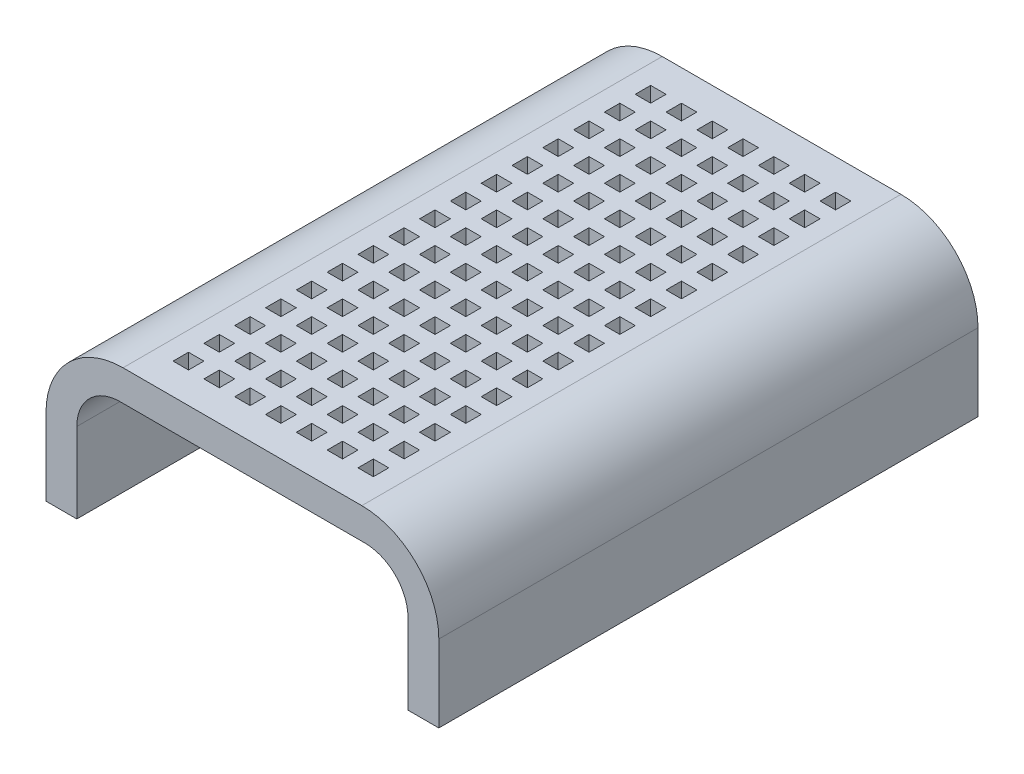
SolidWorks part; units mm, degrees
ref_plane "Plan de face" through (0, 0, 0) normal (0, 0, 1) x (1, 0, 0)
ref_plane "Plan de dessus" through (0, 0, 0) normal (0, 1, 0) x (1, 0, 0)
ref_plane "Plan de droite" through (0, 0, 0) normal (1, 0, 0) x (0, 0, -1)
sketch "Esquisse1" plane through (0, 0, 0) normal (0, 0, 1) x (1, 0, 0)
  line L0 (55, 0) -> (-55, 0) construction
  line L1 (-6.9124, 2) -> (8.5876, 2)
  line L2 (-11.9124, -3) -> (-11.9124, -8)
  line L3 (-11.9124, -8) -> (13.5876, -8)
  line L4 (13.5876, -3) -> (13.5876, -8)
  arc A0 (-6.9124, 2) -> (-11.9124, -3) centre (-6.9124, -3) ccw
  arc A1 (8.5876, 2) -> (13.5876, -3) centre (8.5876, -3) cw
  point P8 (13.5876, 2)
  point P19 (11.5876, 0)
  dimension "D3" = 5
  dimension "D4" = 5
  dimension "D1" = 25.5
  dimension "D2" = 10
extrude "Boss.-Extru.2" add sketch "Esquisse1" against normal blind 35 contours L2 A0 L1 A1 L4 L3
sketch "Esquisse2" plane through (0, 0, 0) normal (0, 0, 1) x (1, 0, 0)
  line L8 (-11.9124, -3) -> (-11.9124, -8) construction
  line L9 (-9.9124, -8) -> (11.5876, -8)
  line L10 (-9.9124, -8) -> (-9.9124, 0)
  line L11 (-9.9124, 0) -> (11.5876, 0)
  line L12 (11.5876, -8) -> (11.5876, 0)
  line L13 (-6.9124, 2) -> (8.5876, 2) construction
  line L14 (13.5876, -3) -> (13.5876, -8) construction
  line L15 (-11.9124, -8) -> (13.5876, -8) construction
  dimension "D1" = 2
  dimension "D2" = 2
  dimension "D3" = 2
extrude "Enlèv. mat.-Extru.1" cut sketch "Esquisse2" against normal up to surface (35 mm away) up to face at (0.8376, -2.6548, -35)
fillet "Congé1" radius 2.8 2 edges at (-9.9124, 0, -17.5) (11.5876, 0, -17.5)
sketch "Esquisse3" plane through (0, 2, 0) normal (0, 1, 0) x (1, 0, 0)
  line L0 (-6.9124, 35) -> (-6.9124, 0) construction
  line L1 (-5.6624, 33) -> (-4.6624, 33)
  line L2 (-5.6624, 33) -> (-5.6624, 32)
  line L3 (-5.6624, 32) -> (-4.6624, 32)
  line L4 (-4.6624, 33) -> (-4.6624, 32)
  line L6 (-3.6624, 33) -> (-3.6624, 32)
  line L7 (-6.9124, 35) -> (8.5876, 35) construction
  line L8 (-3.6624, 33) -> (-2.6624, 33)
  line L9 (-2.6624, 33) -> (-2.6624, 32)
  line L10 (-3.6624, 32) -> (-2.6624, 32)
  line L11 (-1.6624, 33) -> (-1.6624, 32)
  line L12 (-1.6624, 33) -> (-0.6624, 33)
  line L13 (-0.6624, 33) -> (-0.6624, 32)
  line L14 (-1.6624, 32) -> (-0.6624, 32)
  line L15 (0.3376, 33) -> (0.3376, 32)
  line L16 (0.3376, 33) -> (1.3376, 33)
  line L17 (1.3376, 33) -> (1.3376, 32)
  line L18 (0.3376, 32) -> (1.3376, 32)
  line L19 (2.3376, 33) -> (2.3376, 32)
  line L20 (2.3376, 33) -> (3.3376, 33)
  line L21 (3.3376, 33) -> (3.3376, 32)
  line L22 (2.3376, 32) -> (3.3376, 32)
  line L23 (4.3376, 33) -> (4.3376, 32)
  line L24 (4.3376, 33) -> (5.3376, 33)
  line L25 (5.3376, 33) -> (5.3376, 32)
  line L26 (4.3376, 32) -> (5.3376, 32)
  line L27 (6.3376, 33) -> (6.3376, 32)
  line L28 (6.3376, 33) -> (7.3376, 33)
  line L29 (7.3376, 33) -> (7.3376, 32)
  line L30 (6.3376, 32) -> (7.3376, 32)
  line L31 (-3.6624, 31) -> (-3.6624, 30)
  line L32 (-3.6624, 31) -> (-2.6624, 31)
  line L33 (-2.6624, 31) -> (-2.6624, 30)
  line L34 (-3.6624, 30) -> (-2.6624, 30)
  line L35 (-1.6624, 31) -> (-1.6624, 30)
  line L36 (-1.6624, 31) -> (-0.6624, 31)
  line L37 (-0.6624, 31) -> (-0.6624, 30)
  line L38 (-1.6624, 30) -> (-0.6624, 30)
  line L39 (0.3376, 31) -> (0.3376, 30)
  line L40 (0.3376, 31) -> (1.3376, 31)
  line L41 (1.3376, 31) -> (1.3376, 30)
  line L42 (0.3376, 30) -> (1.3376, 30)
  line L43 (2.3376, 31) -> (2.3376, 30)
  line L44 (2.3376, 31) -> (3.3376, 31)
  line L45 (3.3376, 31) -> (3.3376, 30)
  line L46 (2.3376, 30) -> (3.3376, 30)
  line L47 (4.3376, 31) -> (4.3376, 30)
  line L48 (4.3376, 31) -> (5.3376, 31)
  line L49 (5.3376, 31) -> (5.3376, 30)
  line L50 (4.3376, 30) -> (5.3376, 30)
  line L51 (6.3376, 31) -> (6.3376, 30)
  line L52 (6.3376, 31) -> (7.3376, 31)
  line L53 (7.3376, 31) -> (7.3376, 30)
  line L54 (6.3376, 30) -> (7.3376, 30)
  line L55 (-3.6624, 29) -> (-3.6624, 28)
  line L56 (-3.6624, 29) -> (-2.6624, 29)
  line L57 (-2.6624, 29) -> (-2.6624, 28)
  line L58 (-3.6624, 28) -> (-2.6624, 28)
  line L59 (-1.6624, 29) -> (-1.6624, 28)
  line L60 (-1.6624, 29) -> (-0.6624, 29)
  line L61 (-0.6624, 29) -> (-0.6624, 28)
  line L62 (-1.6624, 28) -> (-0.6624, 28)
  line L63 (0.3376, 29) -> (0.3376, 28)
  line L64 (0.3376, 29) -> (1.3376, 29)
  line L65 (1.3376, 29) -> (1.3376, 28)
  line L66 (0.3376, 28) -> (1.3376, 28)
  line L67 (2.3376, 29) -> (2.3376, 28)
  line L68 (2.3376, 29) -> (3.3376, 29)
  line L69 (3.3376, 29) -> (3.3376, 28)
  line L70 (2.3376, 28) -> (3.3376, 28)
  line L71 (4.3376, 29) -> (4.3376, 28)
  line L72 (4.3376, 29) -> (5.3376, 29)
  line L73 (5.3376, 29) -> (5.3376, 28)
  line L74 (4.3376, 28) -> (5.3376, 28)
  line L75 (6.3376, 29) -> (6.3376, 28)
  line L76 (6.3376, 29) -> (7.3376, 29)
  line L77 (7.3376, 29) -> (7.3376, 28)
  line L78 (6.3376, 28) -> (7.3376, 28)
  line L79 (-3.6624, 27) -> (-3.6624, 26)
  line L80 (-3.6624, 27) -> (-2.6624, 27)
  line L81 (-2.6624, 27) -> (-2.6624, 26)
  line L82 (-3.6624, 26) -> (-2.6624, 26)
  line L83 (-1.6624, 27) -> (-1.6624, 26)
  line L84 (-1.6624, 27) -> (-0.6624, 27)
  line L85 (-0.6624, 27) -> (-0.6624, 26)
  line L86 (-1.6624, 26) -> (-0.6624, 26)
  line L87 (0.3376, 27) -> (0.3376, 26)
  line L88 (0.3376, 27) -> (1.3376, 27)
  line L89 (1.3376, 27) -> (1.3376, 26)
  line L90 (0.3376, 26) -> (1.3376, 26)
  line L91 (2.3376, 27) -> (2.3376, 26)
  line L92 (2.3376, 27) -> (3.3376, 27)
  line L93 (3.3376, 27) -> (3.3376, 26)
  line L94 (2.3376, 26) -> (3.3376, 26)
  line L95 (4.3376, 27) -> (4.3376, 26)
  line L96 (4.3376, 27) -> (5.3376, 27)
  line L97 (5.3376, 27) -> (5.3376, 26)
  line L98 (4.3376, 26) -> (5.3376, 26)
  line L99 (6.3376, 27) -> (6.3376, 26)
  line L100 (6.3376, 27) -> (7.3376, 27)
  line L101 (7.3376, 27) -> (7.3376, 26)
  line L102 (6.3376, 26) -> (7.3376, 26)
  line L103 (-3.6624, 25) -> (-3.6624, 24)
  line L104 (-3.6624, 25) -> (-2.6624, 25)
  line L105 (-2.6624, 25) -> (-2.6624, 24)
  line L106 (-3.6624, 24) -> (-2.6624, 24)
  line L107 (-1.6624, 25) -> (-1.6624, 24)
  line L108 (-1.6624, 25) -> (-0.6624, 25)
  line L109 (-0.6624, 25) -> (-0.6624, 24)
  line L110 (-1.6624, 24) -> (-0.6624, 24)
  line L111 (0.3376, 25) -> (0.3376, 24)
  line L112 (0.3376, 25) -> (1.3376, 25)
  line L113 (1.3376, 25) -> (1.3376, 24)
  line L114 (0.3376, 24) -> (1.3376, 24)
  line L115 (2.3376, 25) -> (2.3376, 24)
  line L116 (2.3376, 25) -> (3.3376, 25)
  line L117 (3.3376, 25) -> (3.3376, 24)
  line L118 (2.3376, 24) -> (3.3376, 24)
  line L119 (4.3376, 25) -> (4.3376, 24)
  line L120 (4.3376, 25) -> (5.3376, 25)
  line L121 (5.3376, 25) -> (5.3376, 24)
  line L122 (4.3376, 24) -> (5.3376, 24)
  line L123 (6.3376, 25) -> (6.3376, 24)
  line L124 (6.3376, 25) -> (7.3376, 25)
  line L125 (7.3376, 25) -> (7.3376, 24)
  line L126 (6.3376, 24) -> (7.3376, 24)
  line L127 (-3.6624, 23) -> (-3.6624, 22)
  line L128 (-3.6624, 23) -> (-2.6624, 23)
  line L129 (-2.6624, 23) -> (-2.6624, 22)
  line L130 (-3.6624, 22) -> (-2.6624, 22)
  line L131 (-1.6624, 23) -> (-1.6624, 22)
  line L132 (-1.6624, 23) -> (-0.6624, 23)
  line L133 (-0.6624, 23) -> (-0.6624, 22)
  line L134 (-1.6624, 22) -> (-0.6624, 22)
  line L135 (0.3376, 23) -> (0.3376, 22)
  line L136 (0.3376, 23) -> (1.3376, 23)
  line L137 (1.3376, 23) -> (1.3376, 22)
  line L138 (0.3376, 22) -> (1.3376, 22)
  line L139 (2.3376, 23) -> (2.3376, 22)
  line L140 (2.3376, 23) -> (3.3376, 23)
  line L141 (3.3376, 23) -> (3.3376, 22)
  line L142 (2.3376, 22) -> (3.3376, 22)
  line L143 (4.3376, 23) -> (4.3376, 22)
  line L144 (4.3376, 23) -> (5.3376, 23)
  line L145 (5.3376, 23) -> (5.3376, 22)
  line L146 (4.3376, 22) -> (5.3376, 22)
  line L147 (6.3376, 23) -> (6.3376, 22)
  line L148 (6.3376, 23) -> (7.3376, 23)
  line L149 (7.3376, 23) -> (7.3376, 22)
  line L150 (6.3376, 22) -> (7.3376, 22)
  line L151 (-3.6624, 21) -> (-3.6624, 20)
  line L152 (-3.6624, 21) -> (-2.6624, 21)
  line L153 (-2.6624, 21) -> (-2.6624, 20)
  line L154 (-3.6624, 20) -> (-2.6624, 20)
  line L155 (-1.6624, 21) -> (-1.6624, 20)
  line L156 (-1.6624, 21) -> (-0.6624, 21)
  line L157 (-0.6624, 21) -> (-0.6624, 20)
  line L158 (-1.6624, 20) -> (-0.6624, 20)
  line L159 (0.3376, 21) -> (0.3376, 20)
  line L160 (0.3376, 21) -> (1.3376, 21)
  line L161 (1.3376, 21) -> (1.3376, 20)
  line L162 (0.3376, 20) -> (1.3376, 20)
  line L163 (2.3376, 21) -> (2.3376, 20)
  line L164 (2.3376, 21) -> (3.3376, 21)
  line L165 (3.3376, 21) -> (3.3376, 20)
  line L166 (2.3376, 20) -> (3.3376, 20)
  line L167 (4.3376, 21) -> (4.3376, 20)
  line L168 (4.3376, 21) -> (5.3376, 21)
  line L169 (5.3376, 21) -> (5.3376, 20)
  line L170 (4.3376, 20) -> (5.3376, 20)
  line L171 (6.3376, 21) -> (6.3376, 20)
  line L172 (6.3376, 21) -> (7.3376, 21)
  line L173 (7.3376, 21) -> (7.3376, 20)
  line L174 (6.3376, 20) -> (7.3376, 20)
  line L175 (-3.6624, 19) -> (-3.6624, 18)
  line L176 (-3.6624, 19) -> (-2.6624, 19)
  line L177 (-2.6624, 19) -> (-2.6624, 18)
  line L178 (-3.6624, 18) -> (-2.6624, 18)
  line L179 (-1.6624, 19) -> (-1.6624, 18)
  line L180 (-1.6624, 19) -> (-0.6624, 19)
  line L181 (-0.6624, 19) -> (-0.6624, 18)
  line L182 (-1.6624, 18) -> (-0.6624, 18)
  line L183 (0.3376, 19) -> (0.3376, 18)
  line L184 (0.3376, 19) -> (1.3376, 19)
  line L185 (1.3376, 19) -> (1.3376, 18)
  line L186 (0.3376, 18) -> (1.3376, 18)
  line L187 (2.3376, 19) -> (2.3376, 18)
  line L188 (2.3376, 19) -> (3.3376, 19)
  line L189 (3.3376, 19) -> (3.3376, 18)
  line L190 (2.3376, 18) -> (3.3376, 18)
  line L191 (4.3376, 19) -> (4.3376, 18)
  line L192 (4.3376, 19) -> (5.3376, 19)
  line L193 (5.3376, 19) -> (5.3376, 18)
  line L194 (4.3376, 18) -> (5.3376, 18)
  line L195 (6.3376, 19) -> (6.3376, 18)
  line L196 (6.3376, 19) -> (7.3376, 19)
  line L197 (7.3376, 19) -> (7.3376, 18)
  line L198 (6.3376, 18) -> (7.3376, 18)
  line L199 (-3.6624, 17) -> (-3.6624, 16)
  line L200 (-3.6624, 17) -> (-2.6624, 17)
  line L201 (-2.6624, 17) -> (-2.6624, 16)
  line L202 (-3.6624, 16) -> (-2.6624, 16)
  line L203 (-1.6624, 17) -> (-1.6624, 16)
  line L204 (-1.6624, 17) -> (-0.6624, 17)
  line L205 (-0.6624, 17) -> (-0.6624, 16)
  line L206 (-1.6624, 16) -> (-0.6624, 16)
  line L207 (0.3376, 17) -> (0.3376, 16)
  line L208 (0.3376, 17) -> (1.3376, 17)
  line L209 (1.3376, 17) -> (1.3376, 16)
  line L210 (0.3376, 16) -> (1.3376, 16)
  line L211 (2.3376, 17) -> (2.3376, 16)
  line L212 (2.3376, 17) -> (3.3376, 17)
  line L213 (3.3376, 17) -> (3.3376, 16)
  line L214 (2.3376, 16) -> (3.3376, 16)
  line L215 (4.3376, 17) -> (4.3376, 16)
  line L216 (4.3376, 17) -> (5.3376, 17)
  line L217 (5.3376, 17) -> (5.3376, 16)
  line L218 (4.3376, 16) -> (5.3376, 16)
  line L219 (6.3376, 17) -> (6.3376, 16)
  line L220 (6.3376, 17) -> (7.3376, 17)
  line L221 (7.3376, 17) -> (7.3376, 16)
  line L222 (6.3376, 16) -> (7.3376, 16)
  line L223 (-3.6624, 15) -> (-3.6624, 14)
  line L224 (-3.6624, 15) -> (-2.6624, 15)
  line L225 (-2.6624, 15) -> (-2.6624, 14)
  line L226 (-3.6624, 14) -> (-2.6624, 14)
  line L227 (-1.6624, 15) -> (-1.6624, 14)
  line L228 (-1.6624, 15) -> (-0.6624, 15)
  line L229 (-0.6624, 15) -> (-0.6624, 14)
  line L230 (-1.6624, 14) -> (-0.6624, 14)
  line L231 (0.3376, 15) -> (0.3376, 14)
  line L232 (0.3376, 15) -> (1.3376, 15)
  line L233 (1.3376, 15) -> (1.3376, 14)
  line L234 (0.3376, 14) -> (1.3376, 14)
  line L235 (2.3376, 15) -> (2.3376, 14)
  line L236 (2.3376, 15) -> (3.3376, 15)
  line L237 (3.3376, 15) -> (3.3376, 14)
  line L238 (2.3376, 14) -> (3.3376, 14)
  line L239 (4.3376, 15) -> (4.3376, 14)
  line L240 (4.3376, 15) -> (5.3376, 15)
  line L241 (5.3376, 15) -> (5.3376, 14)
  line L242 (4.3376, 14) -> (5.3376, 14)
  line L243 (6.3376, 15) -> (6.3376, 14)
  line L244 (6.3376, 15) -> (7.3376, 15)
  line L245 (7.3376, 15) -> (7.3376, 14)
  line L246 (6.3376, 14) -> (7.3376, 14)
  line L247 (-3.6624, 13) -> (-3.6624, 12)
  line L248 (-3.6624, 13) -> (-2.6624, 13)
  line L249 (-2.6624, 13) -> (-2.6624, 12)
  line L250 (-3.6624, 12) -> (-2.6624, 12)
  line L251 (-1.6624, 13) -> (-1.6624, 12)
  line L252 (-1.6624, 13) -> (-0.6624, 13)
  line L253 (-0.6624, 13) -> (-0.6624, 12)
  line L254 (-1.6624, 12) -> (-0.6624, 12)
  line L255 (0.3376, 13) -> (0.3376, 12)
  line L256 (0.3376, 13) -> (1.3376, 13)
  line L257 (1.3376, 13) -> (1.3376, 12)
  line L258 (0.3376, 12) -> (1.3376, 12)
  line L259 (2.3376, 13) -> (2.3376, 12)
  line L260 (2.3376, 13) -> (3.3376, 13)
  line L261 (3.3376, 13) -> (3.3376, 12)
  line L262 (2.3376, 12) -> (3.3376, 12)
  line L263 (4.3376, 13) -> (4.3376, 12)
  line L264 (4.3376, 13) -> (5.3376, 13)
  line L265 (5.3376, 13) -> (5.3376, 12)
  line L266 (4.3376, 12) -> (5.3376, 12)
  line L267 (6.3376, 13) -> (6.3376, 12)
  line L268 (6.3376, 13) -> (7.3376, 13)
  line L269 (7.3376, 13) -> (7.3376, 12)
  line L270 (6.3376, 12) -> (7.3376, 12)
  line L271 (-3.6624, 11) -> (-3.6624, 10)
  line L272 (-3.6624, 11) -> (-2.6624, 11)
  line L273 (-2.6624, 11) -> (-2.6624, 10)
  line L274 (-3.6624, 10) -> (-2.6624, 10)
  line L275 (-1.6624, 11) -> (-1.6624, 10)
  line L276 (-1.6624, 11) -> (-0.6624, 11)
  line L277 (-0.6624, 11) -> (-0.6624, 10)
  line L278 (-1.6624, 10) -> (-0.6624, 10)
  line L279 (0.3376, 11) -> (0.3376, 10)
  line L280 (0.3376, 11) -> (1.3376, 11)
  line L281 (1.3376, 11) -> (1.3376, 10)
  line L282 (0.3376, 10) -> (1.3376, 10)
  line L283 (2.3376, 11) -> (2.3376, 10)
  line L284 (2.3376, 11) -> (3.3376, 11)
  line L285 (3.3376, 11) -> (3.3376, 10)
  line L286 (2.3376, 10) -> (3.3376, 10)
  line L287 (4.3376, 11) -> (4.3376, 10)
  line L288 (4.3376, 11) -> (5.3376, 11)
  line L289 (5.3376, 11) -> (5.3376, 10)
  line L290 (4.3376, 10) -> (5.3376, 10)
  line L291 (6.3376, 11) -> (6.3376, 10)
  line L292 (6.3376, 11) -> (7.3376, 11)
  line L293 (7.3376, 11) -> (7.3376, 10)
  line L294 (6.3376, 10) -> (7.3376, 10)
  line L295 (-3.6624, 9) -> (-3.6624, 8)
  line L296 (-3.6624, 9) -> (-2.6624, 9)
  line L297 (-2.6624, 9) -> (-2.6624, 8)
  line L298 (-3.6624, 8) -> (-2.6624, 8)
  line L299 (-1.6624, 9) -> (-1.6624, 8)
  line L300 (-1.6624, 9) -> (-0.6624, 9)
  line L301 (-0.6624, 9) -> (-0.6624, 8)
  line L302 (-1.6624, 8) -> (-0.6624, 8)
  line L303 (0.3376, 9) -> (0.3376, 8)
  line L304 (0.3376, 9) -> (1.3376, 9)
  line L305 (1.3376, 9) -> (1.3376, 8)
  line L306 (0.3376, 8) -> (1.3376, 8)
  line L307 (2.3376, 9) -> (2.3376, 8)
  line L308 (2.3376, 9) -> (3.3376, 9)
  line L309 (3.3376, 9) -> (3.3376, 8)
  line L310 (2.3376, 8) -> (3.3376, 8)
  line L311 (4.3376, 9) -> (4.3376, 8)
  line L312 (4.3376, 9) -> (5.3376, 9)
  line L313 (5.3376, 9) -> (5.3376, 8)
  line L314 (4.3376, 8) -> (5.3376, 8)
  line L315 (6.3376, 9) -> (6.3376, 8)
  line L316 (6.3376, 9) -> (7.3376, 9)
  line L317 (7.3376, 9) -> (7.3376, 8)
  line L318 (6.3376, 8) -> (7.3376, 8)
  line L319 (-3.6624, 7) -> (-3.6624, 6)
  line L320 (-3.6624, 7) -> (-2.6624, 7)
  line L321 (-2.6624, 7) -> (-2.6624, 6)
  line L322 (-3.6624, 6) -> (-2.6624, 6)
  line L323 (-1.6624, 7) -> (-1.6624, 6)
  line L324 (-1.6624, 7) -> (-0.6624, 7)
  line L325 (-0.6624, 7) -> (-0.6624, 6)
  line L326 (-1.6624, 6) -> (-0.6624, 6)
  line L327 (0.3376, 7) -> (0.3376, 6)
  line L328 (0.3376, 7) -> (1.3376, 7)
  line L329 (1.3376, 7) -> (1.3376, 6)
  line L330 (0.3376, 6) -> (1.3376, 6)
  line L331 (2.3376, 7) -> (2.3376, 6)
  line L332 (2.3376, 7) -> (3.3376, 7)
  line L333 (3.3376, 7) -> (3.3376, 6)
  line L334 (2.3376, 6) -> (3.3376, 6)
  line L335 (4.3376, 7) -> (4.3376, 6)
  line L336 (4.3376, 7) -> (5.3376, 7)
  line L337 (5.3376, 7) -> (5.3376, 6)
  line L338 (4.3376, 6) -> (5.3376, 6)
  line L339 (6.3376, 7) -> (6.3376, 6)
  line L340 (6.3376, 7) -> (7.3376, 7)
  line L341 (7.3376, 7) -> (7.3376, 6)
  line L342 (6.3376, 6) -> (7.3376, 6)
  line L343 (-3.6624, 5) -> (-3.6624, 4)
  line L344 (-3.6624, 5) -> (-2.6624, 5)
  line L345 (-2.6624, 5) -> (-2.6624, 4)
  line L346 (-3.6624, 4) -> (-2.6624, 4)
  line L347 (-1.6624, 5) -> (-1.6624, 4)
  line L348 (-1.6624, 5) -> (-0.6624, 5)
  line L349 (-0.6624, 5) -> (-0.6624, 4)
  line L350 (-1.6624, 4) -> (-0.6624, 4)
  line L351 (0.3376, 5) -> (0.3376, 4)
  line L352 (0.3376, 5) -> (1.3376, 5)
  line L353 (1.3376, 5) -> (1.3376, 4)
  line L354 (0.3376, 4) -> (1.3376, 4)
  line L355 (2.3376, 5) -> (2.3376, 4)
  line L356 (2.3376, 5) -> (3.3376, 5)
  line L357 (3.3376, 5) -> (3.3376, 4)
  line L358 (2.3376, 4) -> (3.3376, 4)
  line L359 (4.3376, 5) -> (4.3376, 4)
  line L360 (4.3376, 5) -> (5.3376, 5)
  line L361 (5.3376, 5) -> (5.3376, 4)
  line L362 (4.3376, 4) -> (5.3376, 4)
  line L363 (6.3376, 5) -> (6.3376, 4)
  line L364 (6.3376, 5) -> (7.3376, 5)
  line L365 (7.3376, 5) -> (7.3376, 4)
  line L366 (6.3376, 4) -> (7.3376, 4)
  line L367 (-3.6624, 3) -> (-3.6624, 2)
  line L368 (-3.6624, 3) -> (-2.6624, 3)
  line L369 (-2.6624, 3) -> (-2.6624, 2)
  line L370 (-3.6624, 2) -> (-2.6624, 2)
  line L371 (-1.6624, 3) -> (-1.6624, 2)
  line L372 (-1.6624, 3) -> (-0.6624, 3)
  line L373 (-0.6624, 3) -> (-0.6624, 2)
  line L374 (-1.6624, 2) -> (-0.6624, 2)
  line L375 (0.3376, 3) -> (0.3376, 2)
  line L376 (0.3376, 3) -> (1.3376, 3)
  line L377 (1.3376, 3) -> (1.3376, 2)
  line L378 (0.3376, 2) -> (1.3376, 2)
  line L379 (2.3376, 3) -> (2.3376, 2)
  line L380 (2.3376, 3) -> (3.3376, 3)
  line L381 (3.3376, 3) -> (3.3376, 2)
  line L382 (2.3376, 2) -> (3.3376, 2)
  line L383 (4.3376, 3) -> (4.3376, 2)
  line L384 (4.3376, 3) -> (5.3376, 3)
  line L385 (5.3376, 3) -> (5.3376, 2)
  line L386 (4.3376, 2) -> (5.3376, 2)
  line L387 (6.3376, 3) -> (6.3376, 2)
  line L388 (6.3376, 3) -> (7.3376, 3)
  line L389 (7.3376, 3) -> (7.3376, 2)
  line L390 (6.3376, 2) -> (7.3376, 2)
  line L391 (-5.6624, 31) -> (-5.6624, 30)
  line L392 (-5.6624, 31) -> (-4.6624, 31)
  line L393 (-4.6624, 31) -> (-4.6624, 30)
  line L394 (-5.6624, 30) -> (-4.6624, 30)
  line L395 (-5.6624, 29) -> (-5.6624, 28)
  line L396 (-5.6624, 29) -> (-4.6624, 29)
  line L397 (-4.6624, 29) -> (-4.6624, 28)
  line L398 (-5.6624, 28) -> (-4.6624, 28)
  line L399 (-5.6624, 27) -> (-5.6624, 26)
  line L400 (-5.6624, 27) -> (-4.6624, 27)
  line L401 (-4.6624, 27) -> (-4.6624, 26)
  line L402 (-5.6624, 26) -> (-4.6624, 26)
  line L403 (-5.6624, 25) -> (-5.6624, 24)
  line L404 (-5.6624, 25) -> (-4.6624, 25)
  line L405 (-4.6624, 25) -> (-4.6624, 24)
  line L406 (-5.6624, 24) -> (-4.6624, 24)
  line L407 (-5.6624, 23) -> (-5.6624, 22)
  line L408 (-5.6624, 23) -> (-4.6624, 23)
  line L409 (-4.6624, 23) -> (-4.6624, 22)
  line L410 (-5.6624, 22) -> (-4.6624, 22)
  line L411 (-5.6624, 21) -> (-5.6624, 20)
  line L412 (-5.6624, 21) -> (-4.6624, 21)
  line L413 (-4.6624, 21) -> (-4.6624, 20)
  line L414 (-5.6624, 20) -> (-4.6624, 20)
  line L415 (-5.6624, 19) -> (-5.6624, 18)
  line L416 (-5.6624, 19) -> (-4.6624, 19)
  line L417 (-4.6624, 19) -> (-4.6624, 18)
  line L418 (-5.6624, 18) -> (-4.6624, 18)
  line L419 (-5.6624, 17) -> (-5.6624, 16)
  line L420 (-5.6624, 17) -> (-4.6624, 17)
  line L421 (-4.6624, 17) -> (-4.6624, 16)
  line L422 (-5.6624, 16) -> (-4.6624, 16)
  line L423 (-5.6624, 15) -> (-5.6624, 14)
  line L424 (-5.6624, 15) -> (-4.6624, 15)
  line L425 (-4.6624, 15) -> (-4.6624, 14)
  line L426 (-5.6624, 14) -> (-4.6624, 14)
  line L427 (-5.6624, 13) -> (-5.6624, 12)
  line L428 (-5.6624, 13) -> (-4.6624, 13)
  line L429 (-4.6624, 13) -> (-4.6624, 12)
  line L430 (-5.6624, 12) -> (-4.6624, 12)
  line L431 (-5.6624, 11) -> (-5.6624, 10)
  line L432 (-5.6624, 11) -> (-4.6624, 11)
  line L433 (-4.6624, 11) -> (-4.6624, 10)
  line L434 (-5.6624, 10) -> (-4.6624, 10)
  line L435 (-5.6624, 9) -> (-5.6624, 8)
  line L436 (-5.6624, 9) -> (-4.6624, 9)
  line L437 (-4.6624, 9) -> (-4.6624, 8)
  line L438 (-5.6624, 8) -> (-4.6624, 8)
  line L439 (-5.6624, 7) -> (-5.6624, 6)
  line L440 (-5.6624, 7) -> (-4.6624, 7)
  line L441 (-4.6624, 7) -> (-4.6624, 6)
  line L442 (-5.6624, 6) -> (-4.6624, 6)
  line L443 (-5.6624, 5) -> (-5.6624, 4)
  line L444 (-5.6624, 5) -> (-4.6624, 5)
  line L445 (-4.6624, 5) -> (-4.6624, 4)
  line L446 (-5.6624, 4) -> (-4.6624, 4)
  line L447 (-5.6624, 3) -> (-5.6624, 2)
  line L448 (-5.6624, 3) -> (-4.6624, 3)
  line L449 (-4.6624, 3) -> (-4.6624, 2)
  line L450 (-5.6624, 2) -> (-4.6624, 2)
  line L451 (8.5876, 35) -> (8.5876, 0) construction
  line L453 (-5.5, 0) -> (5.5, 0) construction
  dimension "D1" = 1
  dimension "D2" = 1
  dimension "D3" = 2
  dimension "D4" = 16
  dimension "D5" = 1.25
  dimension "D7" = 1.25
  dimension "D8" = 2
  dimension "D6" = 7
extrude "Enlèv. mat.-Extru.2" cut sketch "Esquisse3" against normal up to surface (2 mm away) up to face at (0.8376, 0, -17.5)
